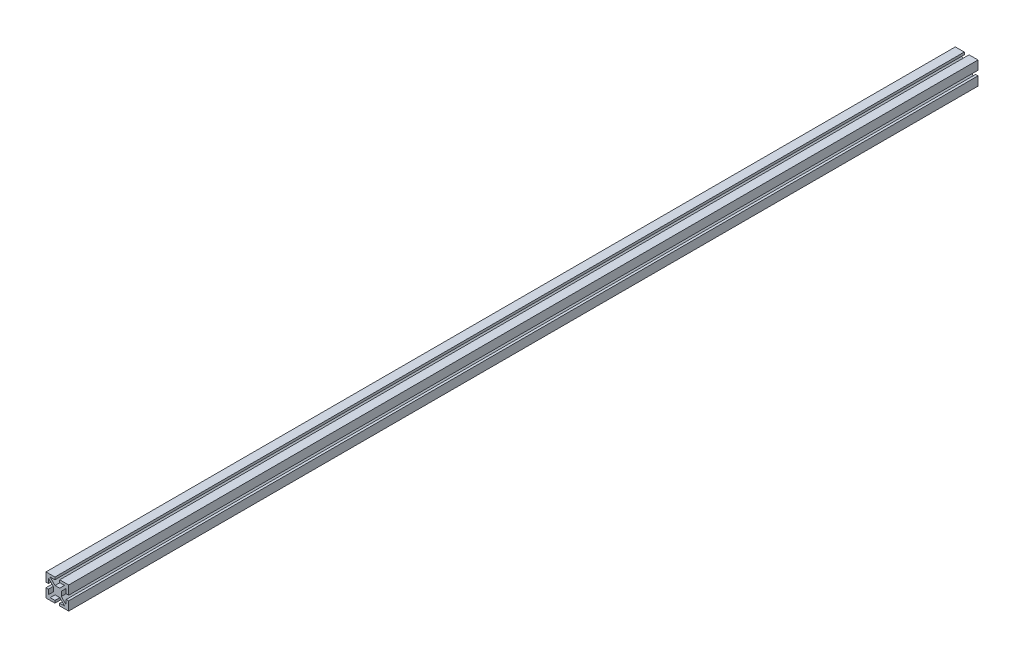
SolidWorks part; units mm, degrees
ref_plane "Front Plane" through (0, 0, 0) normal (0, 0, 1) x (1, 0, 0)
ref_plane "Top Plane" through (0, 0, 0) normal (0, 1, 0) x (1, 0, 0)
ref_plane "Right Plane" through (0, 0, 0) normal (1, 0, 0) x (0, 0, -1)
sketch "Sketch2" plane through (0.5947, -0.5947, 0) normal (0, 0, 1) x (1, 0, 0)
  line L0 (-0.5947, 0.5947) -> (-0.5947, 20.2394) construction
  line L1 (-0.5947, 0.5947) -> (-20.2394, 0.5947) construction
  line L2 (-0.5947, 0.5947) -> (-20.2394, 20.2394) construction
  line L3 (-19.6447, 19.6447) -> (-4.6587, 19.6447)
  line L4 (-4.6587, 19.6447) -> (-4.6587, 15.5807)
  line L5 (-4.6587, 15.5807) -> (-12.707, 15.5807)
  line L6 (-12.707, 15.5807) -> (-4.4774, 7.3511)
  line L7 (-4.4774, 7.3511) -> (3.288, 7.3511)
  line L8 (-19.6447, 19.6447) -> (-19.6447, 4.6587)
  line L9 (-19.6447, 4.6587) -> (-15.5807, 4.6587)
  line L10 (-15.5807, 4.6587) -> (-15.5807, 12.707)
  line L11 (-15.5807, 12.707) -> (-7.3511, 4.4774)
  line L12 (-7.3511, 4.4774) -> (-7.3511, -3.288)
  line L13 (-4.4774, -6.1617) -> (3.288, -6.1617)
  line L14 (-12.707, -14.3913) -> (-4.4774, -6.1617)
  line L15 (-4.6587, -14.3913) -> (-12.707, -14.3913)
  line L16 (-4.6587, -18.4553) -> (-4.6587, -14.3913)
  line L17 (-19.6447, -18.4553) -> (-4.6587, -18.4553)
  line L18 (-19.6447, -18.4553) -> (-19.6447, -3.4693)
  line L19 (-19.6447, -3.4693) -> (-15.5807, -3.4693)
  line L20 (-15.5807, -3.4693) -> (-15.5807, -11.5176)
  line L21 (-15.5807, -11.5176) -> (-7.3511, -3.288)
  line L22 (11.5176, 15.5807) -> (3.288, 7.3511)
  line L23 (3.4693, 15.5807) -> (11.5176, 15.5807)
  line L24 (3.4693, 19.6447) -> (3.4693, 15.5807)
  line L25 (18.4553, 19.6447) -> (3.4693, 19.6447)
  line L26 (18.4553, 19.6447) -> (18.4553, 4.6587)
  line L27 (18.4553, 4.6587) -> (14.3913, 4.6587)
  line L28 (14.3913, 4.6587) -> (14.3913, 12.707)
  line L29 (14.3913, 12.707) -> (6.1617, 4.4774)
  line L30 (6.1617, 4.4774) -> (6.1617, -3.288)
  line L31 (14.3913, -11.5176) -> (6.1617, -3.288)
  line L32 (14.3913, -3.4693) -> (14.3913, -11.5176)
  line L33 (18.4553, -3.4693) -> (14.3913, -3.4693)
  line L34 (18.4553, -18.4553) -> (18.4553, -3.4693)
  line L35 (18.4553, -18.4553) -> (3.4693, -18.4553)
  line L36 (3.4693, -18.4553) -> (3.4693, -14.3913)
  line L37 (3.4693, -14.3913) -> (11.5176, -14.3913)
  line L38 (11.5176, -14.3913) -> (3.288, -6.1617)
  point P26 (-7.3511, 0.5947)
  point P27 (-0.5947, 7.3511)
  point P44 (-0.5947, -6.1617)
  dimension "D1" = 38.1
  dimension "D2" = 8.128
  dimension "D3" = 13.5128
  dimension "D4" = 4.064
  dimension "D5" = 4.064
extrude "Boss-Extrude1" add sketch "Sketch2" along normal up to surface (1528.7625 mm away)
other "1515<1>"
